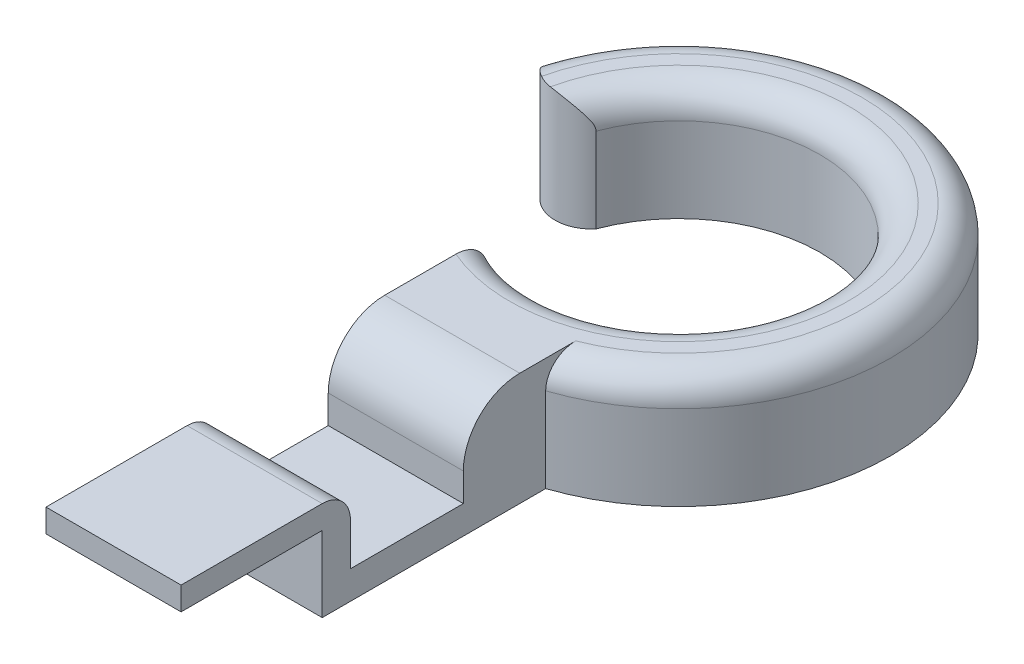
SolidWorks part; units mm, degrees
ref_plane "Front Plane" through (0, 0, 0) normal (0, 0, 1) x (1, 0, 0)
ref_plane "Top Plane" through (0, 0, 0) normal (0, 1, 0) x (1, 0, 0)
ref_plane "Right Plane" through (0, 0, 0) normal (1, 0, 0) x (0, 0, -1)
sketch "Sketch1" plane through (0, 0, 0) normal (0, 1, 0) x (1, 0, 0)
  line L0 (0, -30.9129) -> (0, 25.8244) construction
  line L1 (0, -55) -> (0, 55) construction
  line L4 (-4.786, -8.7803) -> (-4.786, -20.0521)
  line L5 (-4.786, -20.0521) -> (4.786, -20.0521)
  line L6 (4.786, -14.216) -> (4.786, -20.0521)
  line L7 (-4.786, 0.0521) -> (4.786, -20.0521) construction
  line L8 (-4.786, -20.0521) -> (4.786, 0.0521) construction
  arc A1 (-4.786, -8.7803) -> (-9.3654, 3.5056) centre (0, 0) ccw
  arc A2 (-9.3654, 3.5056) -> (-13.891, 5.6603) centre (-11.3484, 5.1706) cw
  arc A3 (4.786, -14.216) -> (-13.891, 5.6603) centre (0, 0) ccw
  point P1 (10, 0)
  point P9 (0, -10)
  point P17 (14.3446, 4.3856)
extrude "Boss-Extrude1" add sketch "Sketch1" along normal blind 8
sketch "Sketch2" plane through (0, 0, 0) normal (0, -1, 0) x (1, 0, 0)
  line L0 (-4.786, 8.7803) -> (-4.786, 20.0521) construction
  line L1 (4.786, 20.0521) -> (-4.786, 20.0521)
  line L2 (4.786, 20.0521) -> (4.786, 30.0521)
  line L3 (4.786, 30.0521) -> (-4.786, 30.0521)
  line L4 (-4.786, 20.0521) -> (-4.786, 30.0521)
  dimension "D1" = 0
  dimension "D2" = 10
extrude "Boss-Extrude2" add sketch "Sketch2" against normal blind 2
sketch "Sketch3" plane through (-4.786, 0, 0) normal (-1, 0, 0) x (0, 0, 1)
  line L0 (30.0521, 2) -> (30.0521, 7)
  line L1 (30.0521, 2) -> (20.0521, 2) construction
  line L2 (28.0521, 2) -> (30.0521, 2)
  line L3 (28.0521, 2) -> (28.0521, 7)
  line L4 (28.0521, 7) -> (30.0521, 7)
  line L5 (30.0521, 2) -> (30.0521, 7)
  line L7 (28.0521, 7) -> (34.0521, 7)
  line L8 (28.0521, 7) -> (28.0521, 5.3521)
  line L9 (28.0521, 5.3521) -> (34.0521, 5.3521)
  line L10 (34.0521, 7) -> (34.0521, 5.3521)
  line M6 (30.0521, 2) -> (20.0521, 2)
  dimension "D1" = 5
  dimension "D2" = 2
  dimension "D3" = 6
extrude "Boss-Extrude3" add sketch "Sketch3" against normal up to vertex contours L9 L3 L0 M6 | L3 L9 L5 L4
fillet "Fillet1" radius 2 1 edges at (0, 7, 28.0521)
fillet "Fillet2" radius 4 1 edges at (0, 8, 20.0521)
fillet "Fillet3" radius 2 2 edges at (10.9313, 8, -10.2717) (9.3702, 8, -3.4926)
sketch "Sketch4" plane through (0, 0, 34.0521) normal (0, 0, 1) x (1, 0, 0)
  line L4 (-4.786, 7) -> (-4.786, 5.3521)
  line L5 (-4.786, 5.3521) -> (4.786, 5.3521)
  line L6 (4.786, 5.3521) -> (4.786, 7)
  line L7 (4.786, 7) -> (-4.786, 7)
  line L8 (-4.786, 7) -> (-4.786, 5.3521)
  line L9 (-4.786, 5.3521) -> (4.786, 5.3521)
  line L10 (4.786, 5.3521) -> (4.786, 7)
  line L11 (4.786, 7) -> (-4.786, 7)
  dimension "D1" = 0
extrude "Boss-Extrude4" add sketch "Sketch4" along normal blind 6
sketch "Sketch5" plane through (0, 7, 0) normal (0, 1, 0) x (1, 0, 0)
  line L1 (4.786, -40.0521) -> (-4.786, -40.0521)
  line L2 (4.786, -40.0521) -> (4.786, -42.0521)
  line L3 (4.786, -42.0521) -> (-4.786, -42.0521)
  line L4 (-4.786, -40.0521) -> (-4.786, -42.0521)
  dimension "D1" = 2
